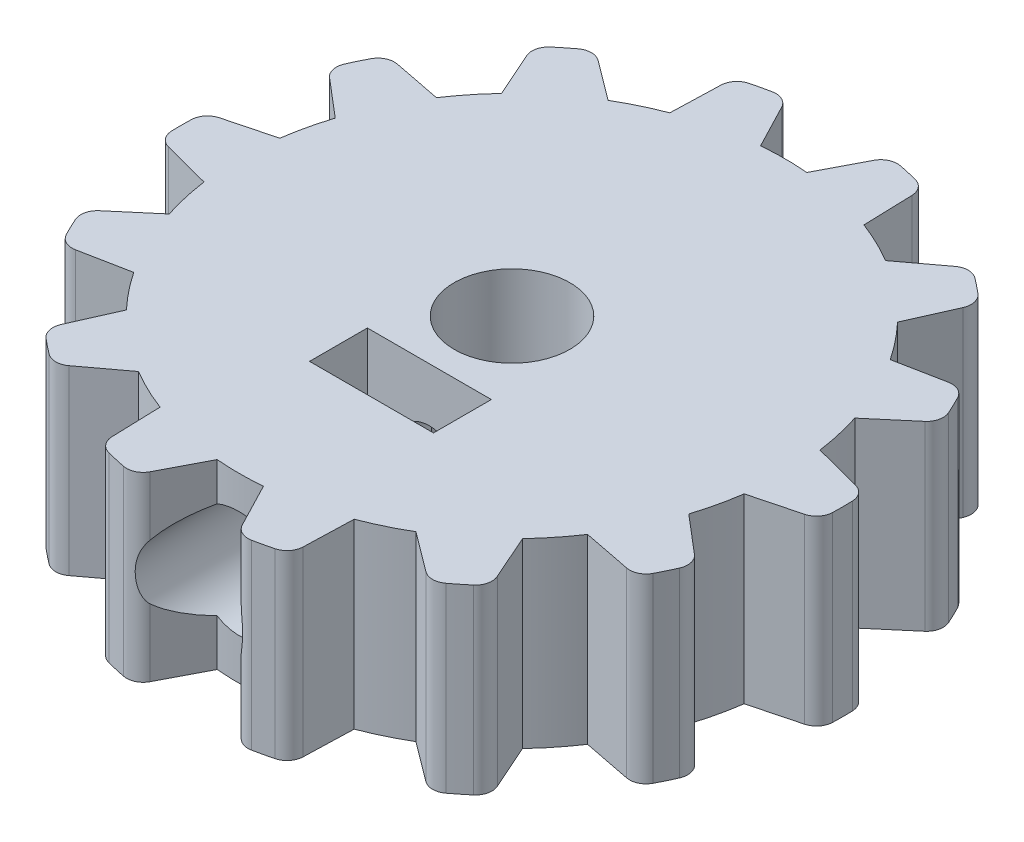
SolidWorks part; units mm, degrees
ref_plane "Front Plane" through (0, 0, 0) normal (0, 0, 1) x (1, 0, 0)
ref_plane "Top Plane" through (0, 0, 0) normal (0, 1, 0) x (1, 0, 0)
ref_plane "Right Plane" through (0, 0, 0) normal (1, 0, 0) x (0, 0, -1)
sketch "Sketch1" plane through (0, 0, 0) normal (0, 1, 0) x (1, 0, 0)
  circle A0 centre (0, 0) radius 20
  dimension "D1" = 40
extrude "Boss-Extrude1" add sketch "Sketch1" along normal blind 11
sketch "Sketch2" plane through (0, 11, 0) normal (0, 1, 0) x (1, 0, 0)
  line L0 (-3.125, 19.7544) -> (-1.3999, 16.4405)
  line L2 (1.3999, 16.4405) -> (3.125, 19.7544)
  circle A0 centre (0, 0) radius 20 construction
  arc A1 (-1.3999, 16.4405) -> (1.3999, 16.4405) centre (0, 0) cw
  arc A2 (3.125, 19.7544) -> (-3.125, 19.7544) centre (0, 0) ccw
  point P6 (0, 16.5)
  dimension "D1" = 16.5
  dimension "D2" = 55
  dimension "D3" = 6.25
extrude "Cut-Extrude1" cut sketch "Sketch2" against normal up to next
fillet "Fillet1" radius 1 2 edges at (3.125, 5.5, -19.7544) (-3.125, 5.5, -19.7544)
pattern_circular "CirPattern1" count 14 over 360 about axis through (0, 0, 0) along (0, 1, 0) of "Cut-Extrude1", "Fillet1"
sketch "Sketch3" plane through (0, 11, 0) normal (0, 1, 0) x (1, 0, 0)
  circle A0 centre (0, 0) radius 3.5
  dimension "D1" = 3.5
extrude "Cut-Extrude2" cut sketch "Sketch3" against normal up to next
sketch "Sketch4" plane through (0, 11, 0) normal (0, 1, 0) x (1, 0, 0)
  line L1 (-3.75, -5) -> (3.75, -5)
  line L2 (-3.75, -5) -> (-3.75, -8.5)
  line L3 (-3.75, -8.5) -> (3.75, -8.5)
  line L4 (3.75, -5) -> (3.75, -8.5)
  point P4 (0, -5)
  dimension "D1" = 5
  dimension "D2" = 3.5
  dimension "D3" = 7.5
extrude "Cut-Extrude3" cut sketch "Sketch4" against normal blind 9
sketch "Sketch6" plane through (0, 0, 0) normal (1, 0, 0) x (0, 0, -1)
  line L0 (0, 5.75) -> (-29.7973, 5.75) construction
  line L1 (-8.5, 2) -> (-5, 2) construction
  line L2 (0, 5.75) -> (0, 7.75)
  line L3 (0, 7.75) -> (-10, 7.75)
  line L4 (-10, 7.75) -> (-10, 9)
  line L5 (-10, 9) -> (-25, 9)
  line L6 (-25, 9) -> (-25, 5.75)
  line L7 (-25, 5.75) -> (0, 5.75)
  dimension "D1" = 3.75
  dimension "D2" = 4
  dimension "D3" = 6.5
  dimension "D4" = 10
  dimension "D5" = 25
revolve "Cut-Revolve1" cut sketch "Sketch6" angle 360 about L0
